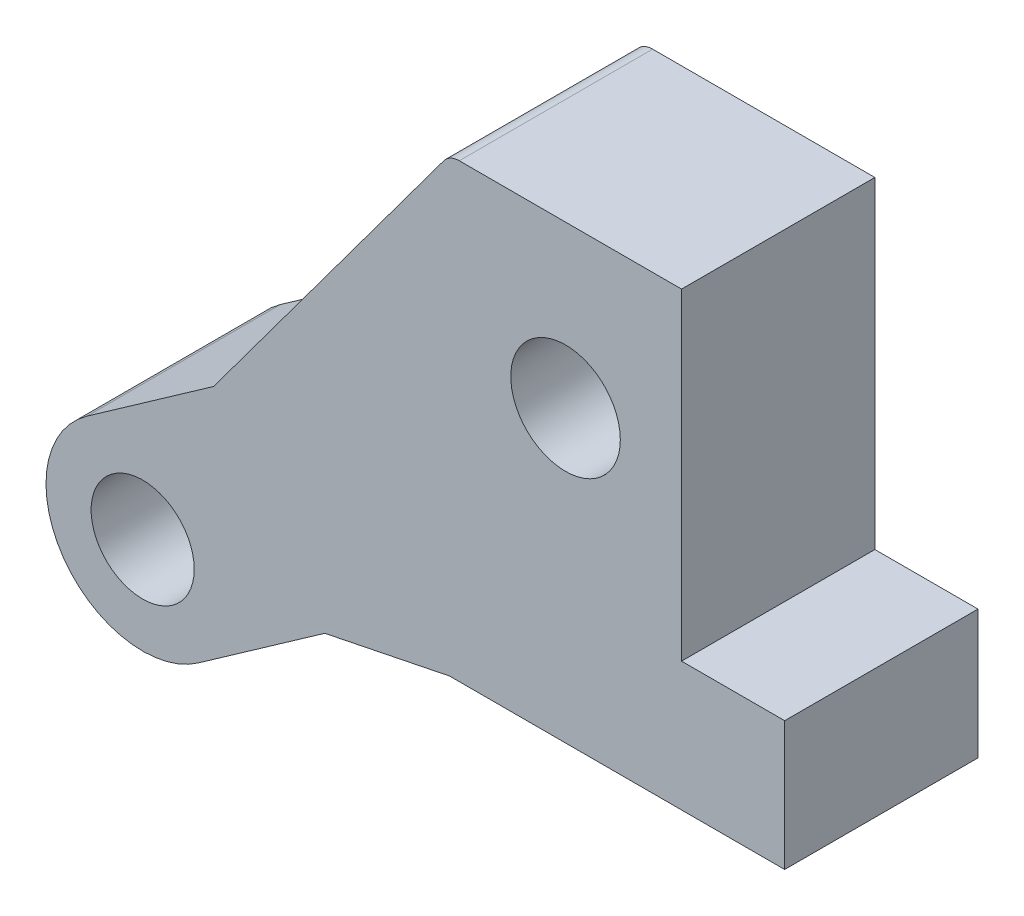
SolidWorks part; units mm, degrees
ref_plane "Front Plane" through (0, 0, 0) normal (0, 0, 1) x (1, 0, 0)
ref_plane "Top Plane" through (0, 0, 0) normal (0, 1, 0) x (1, 0, 0)
ref_plane "Right Plane" through (0, 0, 0) normal (1, 0, 0) x (0, 0, -1)
sketch "Sketch2" plane through (0, 0, 0) normal (0, 0, 1) x (1, 0, 0)
  line L0 (0, 0) -> (0, -35) construction
  line L1 (0, -35) -> (26, -35)
  line L2 (26, -35) -> (26, -25)
  line L3 (26, -25) -> (18, -25)
  line L4 (18, -25) -> (18, 0)
  line L5 (18, 0) -> (0, 0)
  line L6 (9, 0) -> (9, -35) construction
  line L7 (0, -35) -> (-9.6787, -36.9692)
  line L8 (-9.6787, -36.9692) -> (-18.3038, -24.6969) construction
  line L9 (-18.3038, -24.6969) -> (0, 0)
  line L10 (-18.3038, -24.6969) -> (-28.1216, -31.597)
  line L11 (-28.1216, -31.597) -> (-19.4965, -43.8692) construction
  line L12 (-19.4965, -43.8692) -> (-9.6787, -36.9692)
  circle A0 centre (9, -12.5) radius 4.25
  arc A1 (-28.1216, -31.597) -> (-19.4965, -43.8692) centre (-23.8091, -37.7331) ccw
  circle A2 centre (-23.8091, -37.7331) radius 4
  dimension "D5" = 8.5
  dimension "D6" = 12.5
  dimension "D13" = 8
  dimension "D1" = 25
  dimension "D2" = 26
  dimension "D3" = 10
  dimension "D4" = 8
  dimension "D7" = 101.5
  dimension "D8" = 9.877
  dimension "D9" = 113.6
  dimension "D10" = 15
  dimension "D11" = 90
  dimension "D12" = 12
extrude "Boss-Extrude1" add sketch "Sketch2" along normal blind 15
fillet "Fillet1" radius 1.5 1 edges at (0, 0, 7.5)
